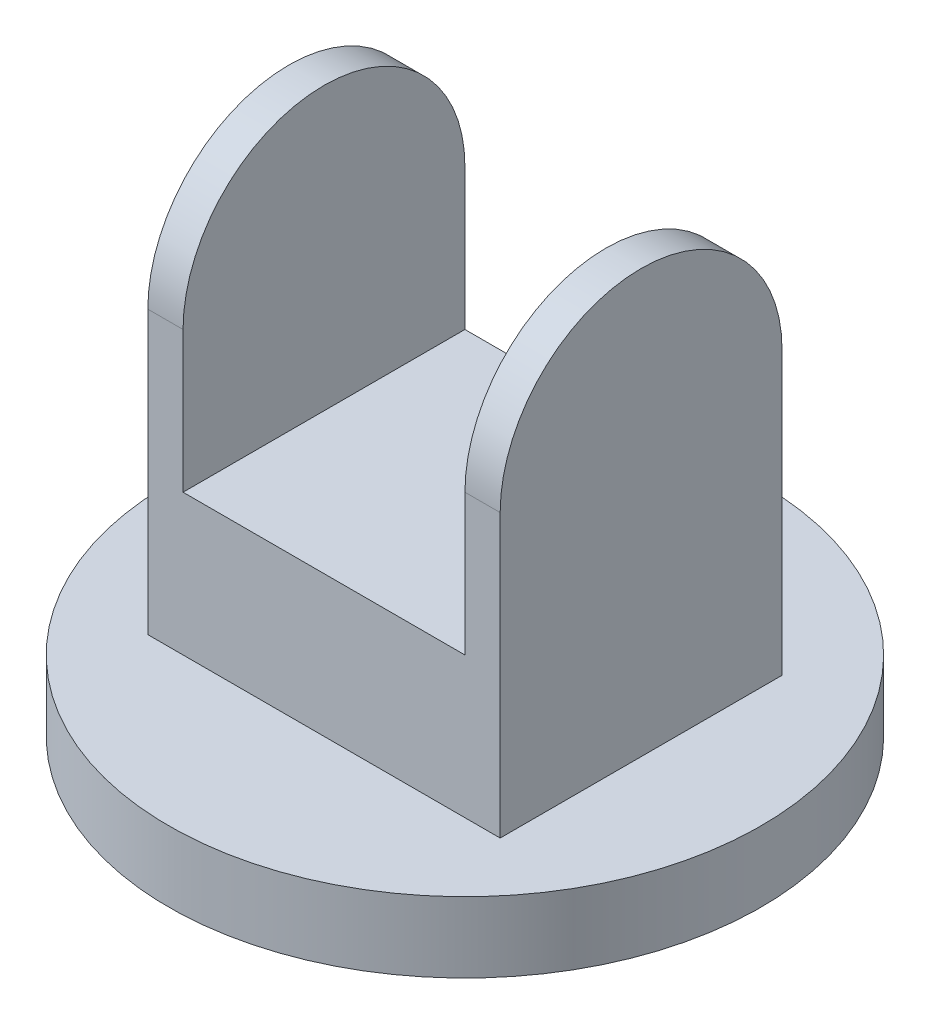
SolidWorks part; units mm, degrees
ref_plane "Front Plane" through (0, 0, 0) normal (0, 0, 1) x (1, 0, 0)
ref_plane "Top Plane" through (0, 0, 0) normal (0, 1, 0) x (1, 0, 0)
ref_plane "Right Plane" through (0, 0, 0) normal (1, 0, 0) x (0, 0, -1)
sketch "Sketch1" plane through (0, 0, 0) normal (1, 0, 0) x (0, 0, -1)
  line L2 (-40, 40) -> (-40, -40)
  line L3 (-40, -40) -> (40, -40)
  line L4 (40, 40) -> (40, -40)
  line L5 (-40, 40) -> (40, -40) construction
  line L6 (-40, -40) -> (40, 40) construction
  arc A1 (40, 40) -> (-40, 40) centre (0, 40) ccw
  point P0 (0, 0)
  dimension "D1" = 80
  dimension "D2" = 80
extrude "Boss-Extrude1" add sketch "Sketch1" along normal blind 100
sketch "Sketch2" plane through (0, -40, 0) normal (0, -1, 0) x (1, 0, 0)
  line L0 (50, -40) -> (50, 40) construction
  line L1 (100, -40) -> (0, -40) construction
  line L2 (100, 40) -> (0, 40) construction
  circle A1 centre (50, 0) radius 84.0312
extrude "Boss-Extrude2" add sketch "Sketch2" along normal blind 20
sketch "Sketch3" plane through (0, 0, 40) normal (0, 0, 1) x (1, 0, 0)
  line L0 (50, 80) -> (50, -40) construction
  line L1 (100, 80) -> (0, 80) construction
  line L2 (100, -40) -> (0, -40) construction
  line L3 (0, 80) -> (0, 40) construction
  line L4 (10, 0) -> (90, 0)
  line L5 (10, 0) -> (10, 80)
  line L6 (10, 80) -> (90, 80)
  line L7 (90, 0) -> (90, 80)
  line L8 (10, 0) -> (90, 80) construction
  line L9 (10, 80) -> (90, 0) construction
  point P6 (50, 40)
  dimension "D1" = 10
  dimension "D2" = 80
  dimension "D3" = 80
extrude "Cut-Extrude1" cut sketch "Sketch3" against normal through all
